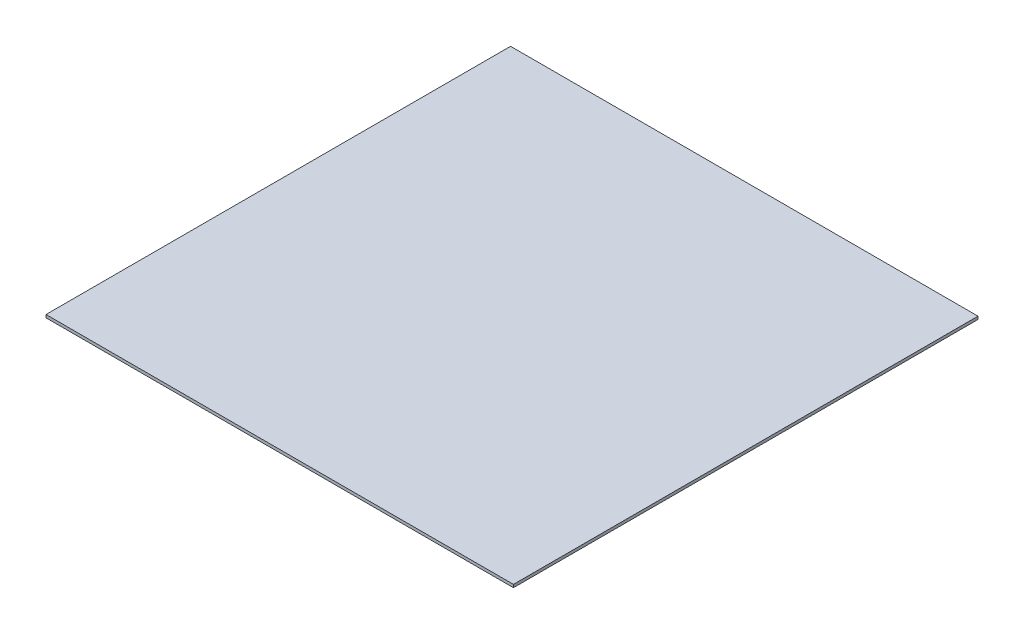
SolidWorks part; units mm, degrees
material "Acrylic (Medium-high impact)"
ref_plane "Front Plane" through (0, 0, 0) normal (0, 0, 1) x (1, 0, 0)
ref_plane "Top Plane" through (0, 0, 0) normal (0, 1, 0) x (1, 0, 0)
ref_plane "Right Plane" through (0, 0, 0) normal (1, 0, 0) x (0, 0, -1)
sketch "Sketch1" plane through (0, 0, 0) normal (0, 1, 0) x (1, 0, 0)
  line L1 (-257.175, -255.5875) -> (257.175, -255.5875)
  line L2 (-257.175, -255.5875) -> (-257.175, 255.5875)
  line L3 (-257.175, 255.5875) -> (257.175, 255.5875)
  line L4 (257.175, -255.5875) -> (257.175, 255.5875)
  line L5 (-257.175, -255.5875) -> (257.175, 255.5875) construction
  line L6 (-257.175, 255.5875) -> (257.175, -255.5875) construction
  point P0 (0, 0)
  dimension "D1" = 514.35
  dimension "D2" = 511.175
extrude "Boss-Extrude1" add sketch "Sketch1" along normal mid plane 3.175
equation "\"BOX PLATE THK\"= .125"
equation "\"D1@Boss-Extrude1\"=\"BOX PLATE THK\""
equation "\"BOX SIZE\"= 20"
equation "\"STANDARD PROFILE\"= 1"
equation "\"D1@Sketch1\"=\"BOX SIZE\"+2*\"BOX PLATE THK\""
equation "\"BIG FACE DEPTH\"= 1.25"
equation "\"BOX DEPTH\"= \"BOX SIZE\"+\"BOX PLATE THK\""
equation "\"D2@Sketch1\"=\"BOX SIZE\"+\"BOX PLATE THK\""
